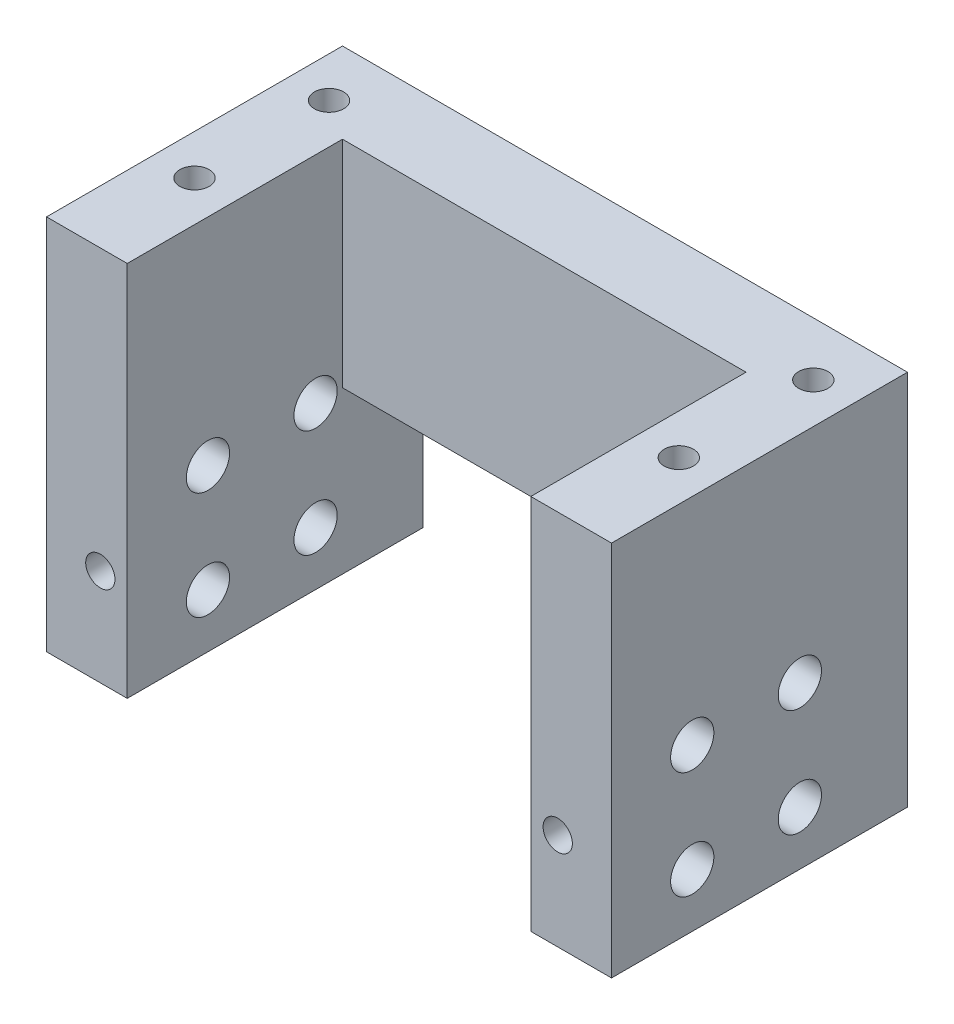
SolidWorks part; units mm, degrees
ref_plane "Front Plane" through (0, 0, 0) normal (0, 0, 1) x (1, 0, 0)
ref_plane "Top Plane" through (0, 0, 0) normal (0, 1, 0) x (1, 0, 0)
ref_plane "Right Plane" through (0, 0, 0) normal (1, 0, 0) x (0, 0, -1)
sketch "Sketch1" plane through (0, 0, 0) normal (0, 1, 0) x (1, 0, 0)
  line L1 (-33.3375, 17.4625) -> (33.3375, 17.4625)
  line L2 (-33.3375, 17.4625) -> (-33.3375, -17.4625)
  line L3 (-33.3375, -17.4625) -> (33.3375, -17.4625)
  line L4 (33.3375, 17.4625) -> (33.3375, -17.4625)
  dimension "D1" = 33.3375
  dimension "D2" = 33.3375
  dimension "D3" = 17.4625
  dimension "D4" = 17.4625
extrude "Boss-Extrude1" add sketch "Sketch1" along normal mid plane 76.2
sketch "Sketch2" plane through (0, 38.1, 0) normal (0, 1, 0) x (1, 0, 0)
  line L0 (-33.3375, -17.4625) -> (33.3375, -17.4625) construction
  line L1 (-23.8125, -17.4625) -> (23.8125, -17.4625)
  line L2 (-23.8125, -17.4625) -> (-23.8125, 7.9375)
  line L3 (-23.8125, 7.9375) -> (23.8125, 7.9375)
  line L4 (23.8125, -17.4625) -> (23.8125, 7.9375)
  line L5 (-33.3375, 17.4625) -> (-33.3375, -17.4625) construction
  line L6 (33.3375, -17.4625) -> (33.3375, 17.4625) construction
  line L7 (33.3375, 17.4625) -> (-33.3375, 17.4625) construction
  dimension "D1" = 9.525
  dimension "D2" = 9.525
  dimension "D3" = 9.525
extrude "Cut-Extrude1" cut sketch "Sketch2" against normal through all
sketch "Sketch3" plane through (33.3375, 0, 0) normal (1, 0, 0) x (0, 0, -1)
  line L0 (-17.4625, 38.1) -> (17.4625, 38.1) construction
  line L1 (-17.4625, -38.1) -> (17.4625, -38.1)
  line L2 (-17.4625, -38.1) -> (-17.4625, -6.35)
  line L3 (-17.4625, -6.35) -> (17.4625, -6.35)
  line L4 (17.4625, -38.1) -> (17.4625, -6.35)
  line L5 (17.4625, 38.1) -> (17.4625, -38.1) construction
  dimension "D1" = 44.45
  dimension "D2" = 0
extrude "Cut-Extrude2" cut sketch "Sketch3" against normal through all
sketch "Sketch4" plane through (0, 0, -17.4625) normal (0, 0, -1) x (-1, 0, 0)
  line L1 (23.8125, -6.35) -> (23.8125, 38.1) construction
  line L2 (23.8125, 12.7) -> (-23.8125, 12.7)
  line L3 (23.8125, 12.7) -> (23.8125, -25.4)
  line L4 (23.8125, -25.4) -> (-23.8125, -25.4)
  line L7 (-23.8125, 12.7) -> (-23.8125, -25.4)
  line L8 (-23.8125, -6.35) -> (-23.8125, 38.1) construction
  line L9 (-23.8125, 38.1) -> (23.8125, 38.1) construction
  dimension "D1" = 25.4
  dimension "D2" = 38.1
extrude "Cut-Extrude3" cut sketch "Sketch4" against normal through all
hole_wizard "1/4-20 Tapped Hole1" positions "Sketch6" profile "Sketch5" tap size "1/4-20" standard "ANSI Inch"
sketch "Sketch6" plane through (33.3375, 0, 0) normal (1, 0, 0) x (0, 0, -1)
  line L0 (-17.4625, 38.1) -> (-17.4625, -6.35) construction
  line L2 (17.4625, 38.1) -> (17.4625, -6.35) construction
  line L3 (17.4625, -6.35) -> (-17.4625, -6.35) construction
  point P0 (-7.9375, 0)
  point P2 (4.7625, 0)
  dimension "D1" = 9.525
  dimension "D2" = 12.7
  dimension "D3" = 6.35
  dimension "D4" = 12.7
sketch "Sketch5" plane through (33.3375, 0, 7.9375) normal (0, 1, 0) x (0, 0, -1)
  line L0 (0, 0) -> (0, 9.526)
  line L1 (0, 9.526) -> (2.5527, 9.526)
  line L2 (2.5527, 9.526) -> (2.5527, 0)
  line L5 (2.5527, 0) -> (0, 0)
  line L11 (0, -6.35) -> (0, 107.95) construction
  dimension "Thru Tap Drill Dia." = 5.1054
  dimension "Thru Tap Drill Depth" = 9.526
cosmetic thread "Hole Thread1" parameters "D2"=6.35
cosmetic thread "Hole Thread2" parameters "D2"=6.35
hole_wizard "#8-32 Tapped Hole1" positions "Sketch8" profile "Sketch7" tap size "#8-32" standard "ANSI Inch"
sketch "Sketch8" plane through (0, 0, 17.4625) normal (0, 0, 1) x (1, 0, 0)
  line L0 (23.8125, -6.35) -> (23.8125, 38.1) construction
  line L1 (23.8125, -6.35) -> (33.3375, -6.35) construction
  point P0 (26.9875, 5.08)
  dimension "D1" = 3.175
  dimension "D2" = 11.43
sketch "Sketch7" plane through (26.9875, 5.08, 17.4625) normal (1, 0, 0) x (0, -1, 0)
  line L0 (0, 0) -> (0, 13.4838)
  line L1 (0, 13.4838) -> (1.7272, 12.446)
  line L2 (1.7272, 12.446) -> (1.7272, 0)
  line L5 (1.7272, 0) -> (0, 0)
  line L10 (0, 13.4838) -> (-1.7272, 12.446) construction
  line L11 (0, -6.35) -> (0, 107.95) construction
  dimension "Tap Drill Dia." = 3.4544
  dimension "Tap Drill Depth" = 12.446
  dimension "Drill Angle" = 118
cosmetic thread "Hole Thread3" parameters "D1"=8.382, "D2"=4.1656
hole_wizard "#8-32 Tapped Hole2" positions "Sketch10" profile "Sketch9" tap size "#8-32" standard "ANSI Inch"
sketch "Sketch10" plane through (0, 38.1, 0) normal (0, 1, 0) x (1, 0, 0)
  line L0 (33.3375, -17.4625) -> (33.3375, 17.4625) construction
  line L1 (23.8125, -17.4625) -> (33.3375, -17.4625) construction
  line L2 (33.3375, 17.4625) -> (-33.3375, 17.4625) construction
  point P0 (28.575, -4.7625)
  point P2 (28.575, 11.1125)
  dimension "D1" = 4.7625
  dimension "D2" = 12.7
  dimension "D3" = 6.35
sketch "Sketch9" plane through (28.575, 38.1, 4.7625) normal (1, 0, 0) x (0, 0, 1)
  line L0 (0, 0) -> (0, 13.4838)
  line L1 (0, 13.4838) -> (1.7272, 12.446)
  line L2 (1.7272, 12.446) -> (1.7272, 0)
  line L5 (1.7272, 0) -> (0, 0)
  line L10 (0, 13.4838) -> (-1.7272, 12.446) construction
  line L11 (0, -6.35) -> (0, 107.95) construction
  dimension "Tap Drill Dia." = 3.4544
  dimension "Tap Drill Depth" = 12.446
  dimension "Drill Angle" = 118
cosmetic thread "Hole Thread4" parameters "D1"=8.382, "D2"=4.1656
cosmetic thread "Hole Thread5" parameters "D1"=8.382, "D2"=4.1656
pattern_linear "LPattern1" count 2 spacing 12.7 along (0, 1, 0) of "1/4-20 Tapped Hole1"
mirror "Mirror1" about plane through (0, 0, 0) normal (1, 0, 0) of "LPattern1", "#8-32 Tapped Hole1", "#8-32 Tapped Hole2", "1/4-20 Tapped Hole1"
